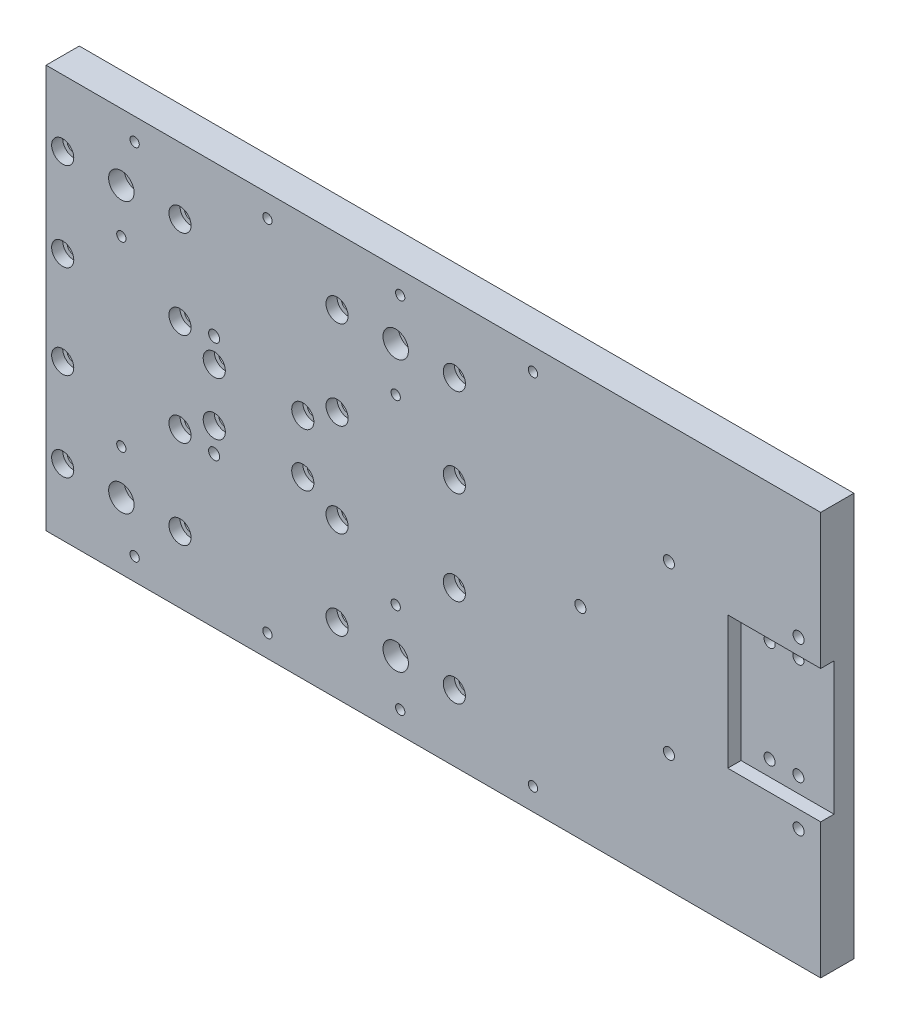
SolidWorks part; units mm, degrees
ref_plane "Default Plane" through (203.2518, -95.6118, 15) normal (0, 0, -1) x (-1, 0, 0)
sketch3d "Bounding-Box_Cut-List-Item1"
  line L0 (350, 0, 0) -> (0, 0, 0) construction
  line L1 (0, 0, 0) -> (0, 182.2, 0) construction
  line L2 (0, 182.2, 0) -> (350, 182.2, 0) construction
  line L3 (350, 182.2, 0) -> (350, 0, 0) construction
  line L4 (350, 0, 15) -> (0, 0, 15) construction
  line L5 (0, 0, 15) -> (0, 182.2, 15) construction
  line L6 (0, 182.2, 15) -> (350, 182.2, 15) construction
  line L7 (350, 182.2, 15) -> (350, 0, 15) construction
  line L8 (350, 0, 0) -> (350, 0, 15) construction
  line L9 (0, 0, 0) -> (0, 0, 15) construction
  line L10 (0, 182.2, 0) -> (0, 182.2, 15) construction
  line L11 (350, 182.2, 0) -> (350, 182.2, 15) construction
material "6061 Alloy"
ref_plane "Front Plane" through (0, 0, 0) normal (0, 0, 1) x (1, 0, 0)
ref_plane "Top Plane" through (0, 0, 0) normal (0, 1, 0) x (1, 0, 0)
ref_plane "Right Plane" through (0, 0, 0) normal (1, 0, 0) x (0, 0, -1)
sketch "Sketch1" plane through (0, 0, 0) normal (0, 0, 1) x (1, 0, 0)
  line L1 (203.2518, 86.5882) -> (-146.7482, 86.5882)
  line L2 (203.2518, 86.5882) -> (203.2518, -95.6118)
  line L3 (203.2518, -95.6118) -> (-146.7482, -95.6118)
  line L4 (-146.7482, 86.5882) -> (-146.7482, -95.6118)
  line L8 (-146.7482, -95.6118) -> (203.2518, -95.6118)
  line L9 (-146.7482, -95.6118) -> (-146.7482, -70.6118)
  line L10 (-146.7482, -70.6118) -> (203.2518, -70.6118)
  line L11 (203.2518, -95.6118) -> (203.2518, -70.6118)
  line L12 (-86.2482, 56.5882) -> (-139.2482, 16.5882) construction
  line L13 (-146.7482, 86.5882) -> (203.2518, 86.5882)
  line L14 (-146.7482, 86.5882) -> (-146.7482, 61.5882)
  line L15 (-146.7482, 61.5882) -> (203.2518, 61.5882)
  line L16 (203.2518, 86.5882) -> (203.2518, 61.5882)
  line L17 (-86.2482, 16.5882) -> (-139.2482, 56.5882) construction
  line L18 (203.2518, -4.5118) -> (-146.7482, -4.5118) construction
  line L19 (37.7183, 56.5882) -> (-15.2817, 16.5882) construction
  line L20 (37.7183, 16.5882) -> (-15.2817, 56.5882) construction
  circle A0 centre (-139.2482, -25.6118) radius 7.5 construction
  circle A1 centre (-86.2482, -65.6118) radius 5 construction
  circle A2 centre (-86.2482, 56.5882) radius 5 construction
  point P33 (11.2183, 36.5882)
  point P34 (-112.7482, 36.5882)
  point P35 (11.2183, -45.6118)
  point P37 (-112.7482, -45.6118)
  point P38 (37.7183, -25.6118)
  point P39 (37.7183, -65.6118)
  point P40 (-15.2817, -65.6118)
  point P41 (-15.2817, -25.6118)
  point P42 (-139.2482, -65.6118)
  point P43 (-86.2482, -25.6118)
  dimension "D3" = 15
  dimension "D4" = 10
  dimension "D2" = 10
  dimension "D1" = 350
  dimension "D5" = 25
  dimension "D6" = 25
  dimension "D7" = 182.2
extrude "Boss-Extrude1" add sketch "Sketch1" along normal blind 15 contours L15 L4 L10 L2 | L4 L15 L2 L1 | L10 L4 L3 L2
sketch "carriageHoleLocations" plane through (0, 0, 15) normal (0, 0, 1) x (1, 0, 0)
  point P0 (37.7183, 56.5882)
  point P2 (37.7183, 16.5882)
  point P4 (11.2183, 36.5882)
  point P6 (-15.2817, 16.5882)
  point P8 (-15.2817, 56.5882)
  point P10 (-139.2482, 56.5882)
  point P12 (-86.2482, 16.5882)
  point P14 (-139.2482, 16.5882)
  point P16 (-112.7482, 36.5882)
  point P18 (-86.2482, 56.5882)
  point P20 (-86.2482, -65.6118)
  point P22 (-139.2482, -65.6118)
  point P24 (-112.7482, -45.6118)
  point P26 (-139.2482, -25.6118)
  point P28 (-86.2482, -25.6118)
  point P30 (-15.2817, -25.6118)
  point P32 (-15.2817, -65.6118)
  point P34 (11.2183, -45.6118)
  point P36 (37.7183, -25.6118)
  point P38 (37.7183, -65.6118)
hole_wizard "carriageHoles" positions "3DSketch3" profile "Sketch5" legacy end condition up to next
sketch3d "3DSketch3"
  point P0 (37.7183, 56.5882, 15)
  point P3 (37.7183, 16.5882, 15)
  point P6 (-15.2817, 16.5882, 15)
  point P9 (-15.2817, 56.5882, 15)
  point P12 (37.7183, -25.6118, 15)
  point P15 (37.7183, -65.6118, 15)
  point P18 (-15.2817, -65.6118, 15)
  point P21 (-15.2817, -25.6118, 15)
  point P24 (-86.2482, -25.6118, 15)
  point P27 (-86.2482, -65.6118, 15)
  point P30 (-139.2482, -65.6118, 15)
  point P33 (-139.2482, -25.6118, 15)
  point P36 (-139.2482, 16.5882, 15)
  point P39 (-86.2482, 16.5882, 15)
  point P42 (-86.2482, 56.5882, 15)
  point P45 (-139.2482, 56.5882, 15)
sketch "Sketch5" plane through (37.7183, 56.5882, 15) normal (1, 0, 0) x (0, -1, 0)
  line L0 (0, 0) -> (0, 15)
  line L1 (0, 15) -> (3, 15)
  line L3 (3, 15) -> (3, 5)
  line L4 (3, 5) -> (5, 5)
  line L5 (5, 5) -> (5, 0)
  line L7 (5, 0) -> (0, 0)
  line L11 (0, -6.35) -> (0, 107.95) construction
  dimension "Thru Hole Dia." = 6
  dimension "Thru Hole Depth" = 15
  dimension "C'Bore Dia." = 10
  dimension "C'Bore Depth" = 5
hole_wizard "carriageSetScrews" positions "3DSketch4" profile "Sketch7" tap size "M5x0.8" standard "ANSI Metric"
sketch3d "3DSketch4"
  point P0 (11.2183, 36.5882, 15)
  point P3 (0, 0, 0)
  point P6 (-112.7482, -45.6118, 15)
  point P9 (-112.7482, 36.5882, 15)
  point P12 (11.2183, -45.6118, 15)
sketch "Sketch7" plane through (11.2183, 36.5882, 15) normal (1, 0, 0) x (0, -1, 0)
  line L0 (0, 0) -> (0, 15)
  line L1 (0, 15) -> (2.1, 15)
  line L2 (2.1, 15) -> (2.1, 0)
  line L5 (2.1, 0) -> (0, 0)
  line L11 (0, -6.35) -> (0, 107.95) construction
  dimension "Thru Tap Drill Dia." = 4.2
  dimension "Thru Tap Drill Depth" = 15
cosmetic thread "Hole Thread1" parameters "D2"=5
cosmetic thread "Hole Thread2" parameters "D2"=5
cosmetic thread "Hole Thread3" parameters "D2"=5
cosmetic thread "Hole Thread4" parameters "D2"=5
cosmetic thread "Hole Thread5" parameters "D2"=5
sketch "railHoles" plane through (0, 0, 15) normal (0, 0, 1) x (1, 0, 0)
  line L0 (103.2518, -92.7536) -> (103.2518, -78.4336) construction
  line L1 (103.2518, -78.4336) -> (-146.7482, -78.4336) construction
  line L2 (-146.7482, -78.4336) -> (-146.7482, -92.7536) construction
  line L3 (-146.7482, -92.7536) -> (103.2518, -92.7536) construction
  line L4 (103.2518, 69.41) -> (103.2518, 83.73) construction
  line L5 (103.2518, 83.73) -> (-146.7482, 83.73) construction
  line L6 (-146.7482, 83.73) -> (-146.7482, 69.41) construction
  line L7 (-146.7482, 69.41) -> (103.2518, 69.41) construction
  line L8 (103.2518, -92.7536) -> (103.2518, -78.4336)
  line L9 (103.2518, -78.4336) -> (-146.7482, -78.4336)
  line L10 (-146.7482, -78.4336) -> (-146.7482, -92.7536)
  line L11 (-146.7482, -92.7536) -> (103.2518, -92.7536)
  line L12 (103.2518, 69.41) -> (103.2518, 83.73)
  line L13 (103.2518, 83.73) -> (-146.7482, 83.73)
  line L14 (-146.7482, 83.73) -> (-146.7482, 69.41)
  line L15 (-146.7482, 69.41) -> (103.2518, 69.41)
  circle A1 centre (73.2518, -85.5936) radius 4.75
  circle A2 centre (73.2518, -85.5936) radius 4.75
  circle A3 centre (13.2518, -85.5936) radius 4.75
  circle A4 centre (13.2518, -85.5936) radius 4.75
  circle A5 centre (-46.7482, -85.5936) radius 4.75
  circle A6 centre (-46.7482, -85.5936) radius 4.75
  circle A7 centre (-106.7482, -85.5936) radius 4.75
  circle A8 centre (-106.7482, -85.5936) radius 4.75
  circle A9 centre (73.2518, 76.57) radius 4.75
  circle A10 centre (73.2518, 76.57) radius 4.75
  circle A11 centre (13.2518, 76.57) radius 4.75
  circle A12 centre (13.2518, 76.57) radius 4.75
  circle A13 centre (-46.7482, 76.57) radius 4.75
  circle A14 centre (-46.7482, 76.57) radius 4.75
  circle A15 centre (-106.7482, 76.57) radius 4.75
  circle A16 centre (-106.7482, 76.57) radius 4.75
  dimension "D1" = 0
  dimension "D2" = 0
  dimension "D3" = 0
  dimension "D4" = 0
  dimension "D5" = 0
  dimension "D6" = 0
  dimension "D7" = 0
  dimension "D8" = 0
hole_wizard "bottomRailHoles" positions "3DSketch5" profile "Sketch9" tap size "M5x0.8" standard "ANSI Metric" end condition up to next
sketch3d "3DSketch5"
  point P0 (-106.7482, 76.57, 15)
  point P3 (-46.7482, 76.57, 15)
  point P6 (13.2518, 76.57, 15)
  point P9 (73.2518, 76.57, 15)
  point P12 (73.2518, -85.5936, 15)
  point P15 (13.2518, -85.5936, 15)
  point P18 (-46.7482, -85.5936, 15)
  point P21 (-106.7482, -85.5936, 15)
sketch "Sketch9" plane through (-106.7482, 76.57, 15) normal (1, 0, 0) x (0, -1, 0)
  line L0 (0, 0) -> (0, 15)
  line L1 (0, 15) -> (2.1, 15)
  line L2 (2.1, 15) -> (2.1, 0)
  line L5 (2.1, 0) -> (0, 0)
  line L11 (0, -6.35) -> (0, 107.95) construction
  dimension "Thru Tap Drill Dia." = 4.2
  dimension "Thru Tap Drill Depth" = 15
cosmetic thread "Hole Thread6" parameters "D2"=5
cosmetic thread "Hole Thread7" parameters "D2"=5
cosmetic thread "Hole Thread8" parameters "D2"=5
cosmetic thread "Hole Thread9" parameters "D2"=5
cosmetic thread "Hole Thread10" parameters "D2"=5
cosmetic thread "Hole Thread11" parameters "D2"=5
cosmetic thread "Hole Thread12" parameters "D2"=5
cosmetic thread "Hole Thread13" parameters "D2"=5
sketch "Sketch10" plane through (0, 0, 0) normal (0, 0, -1) x (-1, 0, 0)
  line L0 (20.2817, -70.8618) -> (81.2482, 61.8382) construction
  line L2 (80.765, -29.5118) -> (20.765, -29.5118)
  line L3 (80.765, -29.5118) -> (80.765, 20.4882)
  line L4 (-203.2518, 86.5882) -> (-203.2518, -95.6118)
  line L5 (-203.2518, -95.6118) -> (146.7482, -95.6118)
  line L6 (146.7482, -95.6118) -> (146.7482, 86.5882)
  line L7 (146.7482, 86.5882) -> (-203.2518, 86.5882)
  line L8 (-203.2518, 86.5882) -> (-203.2518, -95.6118)
  line L9 (-203.2518, -95.6118) -> (146.7482, -95.6118)
  line L10 (146.7482, -95.6118) -> (146.7482, 86.5882)
  line L11 (146.7482, 86.5882) -> (-203.2518, 86.5882)
  line L12 (20.2817, 61.8382) -> (-42.7183, 61.8382)
  line L13 (-42.7183, 61.8382) -> (-42.7183, -70.8618)
  line L14 (-42.7183, -70.8618) -> (20.2817, -70.8618)
  line L15 (20.2817, -70.8618) -> (20.2817, 61.8382)
  line L16 (20.2817, 61.8382) -> (-42.7183, 61.8382)
  line L17 (-42.7183, 61.8382) -> (-42.7183, -70.8618)
  line L18 (-42.7183, -70.8618) -> (20.2817, -70.8618)
  line L19 (20.2817, -70.8618) -> (20.2817, 61.8382)
  line L28 (80.765, 20.4882) -> (20.765, 20.4882)
  line L29 (20.765, -29.5118) -> (20.765, 20.4882)
  line L30 (80.765, -29.5118) -> (20.765, 20.4882) construction
  line L31 (80.765, 20.4882) -> (20.765, -29.5118) construction
  line L56 (20.765, -29.5118) -> (80.765, -29.5118)
  line L57 (20.765, -29.5118) -> (20.765, -44.5118)
  line L58 (20.765, -44.5118) -> (80.765, -44.5118)
  line L59 (80.765, -29.5118) -> (80.765, -44.5118)
  point P10 (50.765, -4.5118)
  dimension "D4" = 60
  dimension "D5" = 50
  dimension "D6" = 15
  dimension "D1" = 0
  dimension "D2" = 0
extrude "Cut-Extrude1" cut sketch "Sketch10" against normal blind 4 contours L29 L2 L3 L28 | L59 L2 L57 L58
sketch "sfuNutHolesLocations" plane through (0, 0, 15) normal (0, 0, 1) x (1, 0, 0)
  line L1 (-20.765, 20.4882) -> (-80.765, -29.5118) construction
  line L2 (-70.765, 7.4882) -> (-30.765, 7.4882) construction
  line L3 (-70.765, 7.4882) -> (-70.765, -16.5118) construction
  line L4 (-20.765, -44.5118) -> (-20.765, 20.4882)
  line L5 (-80.765, -44.5118) -> (-20.765, -44.5118)
  line L6 (-80.765, 20.4882) -> (-80.765, -44.5118)
  line L7 (-20.765, 20.4882) -> (-80.765, 20.4882)
  line L8 (-20.765, -44.5118) -> (-20.765, 20.4882) construction
  line L10 (-80.765, 20.4882) -> (-80.765, -44.5118) construction
  line L11 (-20.765, 20.4882) -> (-80.765, 20.4882) construction
  line L12 (-70.765, -16.5118) -> (-30.765, -16.5118) construction
  line L13 (-30.765, 7.4882) -> (-30.765, -16.5118) construction
  line L14 (-70.765, 7.4882) -> (-30.765, -16.5118) construction
  line L15 (-70.765, -16.5118) -> (-30.765, 7.4882) construction
  line L16 (-80.765, -44.5118) -> (-20.765, -44.5118)
  line L17 (-80.765, -44.5118) -> (-80.765, -29.5118)
  line L18 (-80.765, -29.5118) -> (-20.765, -29.5118)
  line L19 (-80.765, -44.5118) -> (-20.765, -44.5118)
  line L20 (-20.765, -44.5118) -> (-20.765, -29.5118)
  point P2 (-50.765, -4.5118)
  dimension "D2" = 24
  dimension "D3" = 40
  dimension "D4" = 15
  dimension "D1" = 0
hole_wizard "sfuNutHoles" positions "3DSketch6" profile "Sketch12" legacy
sketch3d "3DSketch6"
  point P0 (-30.765, 7.4882, 15)
  point P3 (-30.765, -16.5118, 15)
  point P6 (-70.765, -16.5118, 15)
  point P9 (-70.765, 7.4882, 15)
sketch "Sketch12" plane through (-30.765, 7.4882, 15) normal (1, 0, 0) x (0, -1, 0)
  line L0 (0, 0) -> (0, 12.8026)
  line L1 (0, 12.8026) -> (3, 11)
  line L2 (3, 11) -> (3, 5)
  line L3 (3, 5) -> (5, 5)
  line L4 (5, 5) -> (5, 0)
  line L5 (5, 0) -> (0, 0)
  line L10 (0, 12.8026) -> (-3, 11) construction
  line L11 (0, -6.35) -> (0, 107.95) construction
  dimension "Hole Dia." = 6
  dimension "Hole Depth" = 11
  dimension "C'Bore Dia." = 10
  dimension "C'Bore Depth" = 5
  dimension "Drill Angle" = 118
sketch "Sketch13" plane through (0, 0, 15) normal (0, 0, 1) x (1, 0, 0)
  line L0 (203.2518, -4.5118) -> (99.1965, -4.5118) construction
  line L1 (203.2518, 86.5882) -> (203.2518, -95.6118) construction
  line L3 (203.2518, 25.4882) -> (161.2518, 25.4882)
  line L4 (203.2518, 25.4882) -> (203.2518, -34.5118)
  line L5 (203.2518, -34.5118) -> (161.2518, -34.5118)
  line L6 (161.2518, 25.4882) -> (161.2518, -34.5118)
  point P8 (161.2518, -4.5118)
  dimension "D1" = 60
  dimension "D2" = 42
extrude "bkNotch" cut sketch "Sketch13" against normal blind 6 contours L6 L5 L4 L3
sketch "bkBlockholes" plane through (0, 0, 9) normal (0, 0, 1) x (1, 0, 0)
  circle A4 centre (174.1617, -27.5118) radius 3.5
  circle A5 centre (174.1617, -27.5118) radius 3.5
  circle A6 centre (187.1617, -27.5118) radius 3.5
  circle A7 centre (187.1617, -27.5118) radius 3.5
  circle A8 centre (174.1617, 18.4882) radius 3.5
  circle A9 centre (174.1617, 18.4882) radius 3.5
  circle A10 centre (187.1617, 18.4882) radius 3.5
  circle A11 centre (187.1617, 18.4882) radius 3.5
  dimension "D1" = 0
  dimension "D2" = 0
  dimension "D3" = 0
  dimension "D4" = 0
hole_wizard "M6x1.0 Tapped Hole1" positions "3DSketch7" profile "Sketch16" tap size "M6x1.0" standard "ANSI Metric"
sketch3d "3DSketch7"
  point P0 (187.1617, 18.4882, 9)
  point P3 (174.1617, 18.4882, 9)
  point P6 (187.1617, -27.5118, 9)
  point P9 (174.1617, -27.5118, 9)
sketch "Sketch16" plane through (187.1617, 18.4882, 9) normal (1, 0, 0) x (0, -1, 0)
  line L0 (0, 0) -> (0, 16.5022)
  line L1 (0, 16.5022) -> (2.5, 15)
  line L2 (2.5, 15) -> (2.5, 0)
  line L5 (2.5, 0) -> (0, 0)
  line L10 (0, 16.5022) -> (-2.5, 15) construction
  line L11 (0, -6.35) -> (0, 107.95) construction
  dimension "Tap Drill Dia." = 5
  dimension "Tap Drill Depth" = 15
  dimension "Drill Angle" = 118
cosmetic thread "Hole Thread14" parameters "D1"=12, "D2"=6
cosmetic thread "Hole Thread15" parameters "D1"=12, "D2"=6
cosmetic thread "Hole Thread16" parameters "D1"=12, "D2"=6
cosmetic thread "Hole Thread17" parameters "D1"=12, "D2"=6
sketch "BFBlockHolesLocation" plane through (0, 0, 15) normal (0, 0, 1) x (1, 0, 0)
  line L5 (-79.3383, -21.5118) -> (-79.3383, -33.0118)
  line L6 (-79.3383, -33.0118) -> (-72.5153, -33.0118)
  line L7 (-69.1612, -33.0118) -> (-62.3383, -33.0118)
  line L8 (161.2518, 25.4882) -> (203.2518, 25.4882)
  line L9 (203.2518, 25.4882) -> (203.2518, 86.5882)
  line L10 (203.2518, 86.5882) -> (-146.7482, 86.5882)
  line L11 (-146.7482, 86.5882) -> (-146.7482, -95.6118)
  line L12 (-146.7482, -95.6118) -> (203.2518, -95.6118)
  line L13 (203.2518, -95.6118) -> (203.2518, -34.5118)
  line L14 (203.2518, -34.5118) -> (161.2518, -34.5118)
  line L15 (161.2518, -34.5118) -> (161.2518, 25.4882)
  line L16 (161.2518, 25.4882) -> (203.2518, 25.4882)
  line L17 (203.2518, 25.4882) -> (203.2518, 86.5882)
  line L18 (203.2518, 86.5882) -> (-146.7482, 86.5882)
  line L19 (-146.7482, 86.5882) -> (-146.7482, -95.6118)
  line L20 (-146.7482, -95.6118) -> (203.2518, -95.6118)
  line L21 (203.2518, -95.6118) -> (203.2518, -34.5118)
  line L22 (203.2518, -34.5118) -> (161.2518, -34.5118)
  line L23 (161.2518, -34.5118) -> (161.2518, 25.4882)
  line L24 (-62.3383, -33.0118) -> (-62.3383, -21.5118)
  line L25 (-62.3383, -21.5118) -> (-79.3383, -21.5118)
  line L26 (-79.3383, -21.5118) -> (-79.3383, -33.0118)
  line L27 (-79.3383, -33.0118) -> (-72.5153, -33.0118)
  line L28 (-69.1612, -33.0118) -> (-62.3383, -33.0118)
  line L29 (-62.3383, -33.0118) -> (-62.3383, -21.5118)
  line L30 (-62.3383, -21.5118) -> (-79.3383, -21.5118)
  line L31 (-72.5153, 23.9882) -> (-79.3383, 23.9882)
  line L32 (-79.3383, 23.9882) -> (-79.3383, 12.4882)
  line L33 (-79.3383, 12.4882) -> (-62.3383, 12.4882)
  line L34 (-62.3383, 12.4882) -> (-62.3383, 23.9882)
  line L35 (-62.3383, 23.9882) -> (-69.1612, 23.9882)
  line L36 (-72.5153, 23.9882) -> (-79.3383, 23.9882)
  line L37 (-79.3383, 23.9882) -> (-79.3383, 12.4882)
  line L38 (-79.3383, 12.4882) -> (-62.3383, 12.4882)
  line L39 (-62.3383, 12.4882) -> (-62.3383, 23.9882)
  line L40 (-62.3383, 23.9882) -> (-69.1612, 23.9882)
  arc A3 (-76.5883, -27.5118) -> (-72.5153, -33.0118) centre (-70.8383, -27.5118) ccw
  arc A4 (-65.0883, -27.5118) -> (-76.5883, -27.5118) centre (-70.8383, -27.5118) ccw
  arc A5 (-69.1612, -33.0118) -> (-65.0883, -27.5118) centre (-70.8383, -27.5118) ccw
  arc A6 (-76.5883, -27.5118) -> (-72.5153, -33.0118) centre (-70.8383, -27.5118) ccw
  arc A7 (-65.0883, -27.5118) -> (-76.5883, -27.5118) centre (-70.8383, -27.5118) ccw
  arc A8 (-69.1612, -33.0118) -> (-65.0883, -27.5118) centre (-70.8383, -27.5118) ccw
  arc A9 (-65.0883, 18.4882) -> (-69.1612, 23.9882) centre (-70.8383, 18.4882) ccw
  arc A10 (-76.5883, 18.4882) -> (-65.0883, 18.4882) centre (-70.8383, 18.4882) ccw
  arc A11 (-72.5153, 23.9882) -> (-76.5883, 18.4882) centre (-70.8383, 18.4882) ccw
  arc A12 (-65.0883, 18.4882) -> (-69.1612, 23.9882) centre (-70.8383, 18.4882) ccw
  arc A13 (-76.5883, 18.4882) -> (-65.0883, 18.4882) centre (-70.8383, 18.4882) ccw
  arc A14 (-72.5153, 23.9882) -> (-76.5883, 18.4882) centre (-70.8383, 18.4882) ccw
  dimension "D1" = 0
  dimension "D2" = 0
  dimension "D3" = 0
hole_wizard "BFBlockHoles" positions "3DSketch9" profile "Sketch21" tap size "M6x1.0" standard "ANSI Metric"
sketch3d "3DSketch9"
  point P0 (-70.8383, 18.4882, 15)
  point P3 (-70.8383, -27.5118, 15)
sketch "Sketch21" plane through (-70.8383, 18.4882, 15) normal (1, 0, 0) x (0, -1, 0)
  line L0 (0, 0) -> (0, 11)
  line L1 (0, 11) -> (2.5, 11)
  line L2 (2.5, 11) -> (2.5, 0)
  line L5 (2.5, 0) -> (0, 0)
  line L11 (0, -6.35) -> (0, 107.95) construction
  dimension "Thru Tap Drill Dia." = 5
  dimension "Thru Tap Drill Depth" = 11
cosmetic thread "Hole Thread18" parameters "D2"=6
cosmetic thread "Hole Thread19" parameters "D2"=6
sketch "Sketch22" plane through (0, 0, 0) normal (0, 0, -1) x (-1, 0, 0)
  line L0 (-203.2518, -95.6118) -> (146.7482, -95.6118) construction
  line L1 (20.765, -44.5118) -> (80.765, -44.5118)
  line L2 (20.765, -44.5118) -> (20.765, -95.6118)
  line L3 (20.765, -95.6118) -> (80.765, -95.6118)
  line L4 (80.765, -44.5118) -> (80.765, -95.6118)
extrude "Cut-Extrude2" cut sketch "Sketch22" against normal blind 4
sketch "motorMountLocation" plane through (0, 0, 15) normal (0, 0, 1) x (1, 0, 0)
  circle A0 centre (193.2518, 32.7338) radius 5.5 construction
  circle A1 centre (193.2518, -42.2574) radius 5.5 construction
  circle A2 centre (193.2518, 32.7338) radius 5.5
  circle A3 centre (193.2518, -42.2574) radius 5.5
hole_wizard "MotorMount" positions "3DSketch10" profile "Sketch24" tap size "M6x1.0" standard "ANSI Metric" end condition up to next
sketch3d "3DSketch10"
  point P0 (193.2518, 32.7338, 15)
  point P3 (193.2518, -42.2574, 15)
sketch "Sketch24" plane through (193.2518, 32.7338, 15) normal (1, 0, 0) x (0, -1, 0)
  line L0 (0, 0) -> (0, 15)
  line L1 (0, 15) -> (2.5, 15)
  line L2 (2.5, 15) -> (2.5, 0)
  line L5 (2.5, 0) -> (0, 0)
  line L11 (0, -6.35) -> (0, 107.95) construction
  dimension "Thru Tap Drill Dia." = 5
  dimension "Thru Tap Drill Depth" = 15
cosmetic thread "Hole Thread20" parameters "D2"=6
cosmetic thread "Hole Thread21" parameters "D2"=6
sketch "Sketch25" plane through (0, 0, 15) normal (0, 0, 1) x (1, 0, 0)
  circle A0 centre (11.2183, -65.6118) radius 2.5 construction
  circle A1 centre (11.2183, 56.5882) radius 2.5 construction
  circle A2 centre (11.2183, -65.6118) radius 2.5
  circle A3 centre (11.2183, 56.5882) radius 2.5
  circle A4 centre (-112.7482, 56.5882) radius 2.5 construction
  circle A5 centre (-112.7482, -65.6118) radius 2.5 construction
  circle A6 centre (-112.7482, 56.5882) radius 2.5
  circle A7 centre (-112.7482, -65.6118) radius 2.5
hole_wizard "carriagePlatesScrews" positions "3DSketch11" profile "Sketch27" legacy end condition up to next
sketch3d "3DSketch11"
  point P0 (11.2183, 56.5882, 15)
  point P3 (11.2183, -65.6118, 15)
  point P7 (-112.7482, -65.6118, 15)
  point P10 (-112.7482, 56.5882, 15)
sketch "Sketch27" plane through (11.2183, 56.5882, 15) normal (1, 0, 0) x (0, -1, 0)
  line L0 (0, 0) -> (0, 15)
  line L1 (0, 15) -> (3.3, 15)
  line L3 (3.3, 15) -> (3.3, 7)
  line L4 (3.3, 7) -> (5.75, 7)
  line L5 (5.75, 7) -> (5.75, 0)
  line L7 (5.75, 0) -> (0, 0)
  line L11 (0, -6.35) -> (0, 107.95) construction
  dimension "Thru Hole Dia." = 6.6
  dimension "Thru Hole Depth" = 15
  dimension "C'Bore Dia." = 11.5
  dimension "C'Bore Depth" = 7
sketch "Sketch28" plane through (0, 0, 0) normal (0, 0, -1) x (-1, 0, 0)
  line L0 (-203.2518, -4.5118) -> (-43.1121, -4.5118) construction
  line L1 (-203.2518, 86.5882) -> (-203.2518, -95.6118) construction
  line L2 (-134.6783, -42.0118) -> (-134.6783, 32.9882) construction
  line L3 (-42.7183, 61.8382) -> (-42.7183, -70.8618) construction
  point P6 (-134.6783, -4.5118)
  point P7 (-94.6783, -4.5118)
  dimension "D1" = 75
  dimension "D2" = 40
  dimension "D3" = 91.96
hole_wizard "M6x1.0 Tapped Hole2" positions "3DSketch12" profile "Sketch29" tap size "M6x1.0" standard "ANSI Metric" end condition through all
sketch3d "3DSketch12"
  point P0 (134.6783, -42.0118, 0)
  point P3 (94.6783, -4.5118, 0)
  point P6 (134.6783, 32.9882, 0)
sketch "Sketch29" plane through (134.6783, -42.0118, 0) normal (1, 0, 0) x (0, 1, 0)
  line L0 (0, 0) -> (0, 15)
  line L1 (0, 15) -> (2.5, 15)
  line L2 (2.5, 15) -> (2.5, 0)
  line L5 (2.5, 0) -> (0, 0)
  line L11 (0, -6.35) -> (0, 107.95) construction
  dimension "Thru Tap Drill Dia." = 5
  dimension "Thru Tap Drill Depth" = 15
cosmetic thread "Hole Thread22" parameters "D2"=6
cosmetic thread "Hole Thread23" parameters "D2"=6
cosmetic thread "Hole Thread24" parameters "D2"=6
equation "\"plateHeight\"= 350"
equation "\"plateWidth\"= 15"
equation "\"D1@Sketch1\"= \"plateHeight\""
equation "\"D1@Boss-Extrude1\"= \"plateWidth\""
